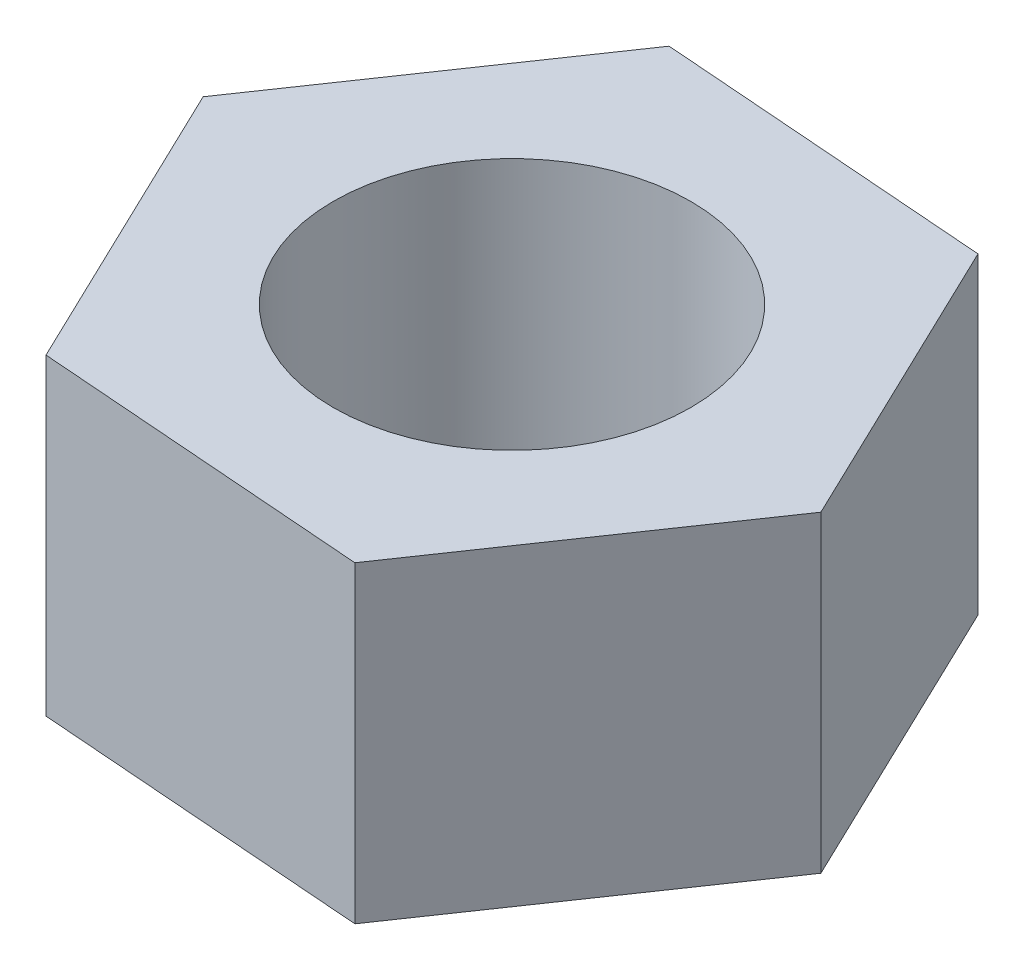
SolidWorks part; units mm, degrees
ref_plane "Спереди" through (0, 0, 0) normal (0, 0, 1) x (1, 0, 0)
ref_plane "Сверху" through (0, 0, 0) normal (0, 1, 0) x (1, 0, 0)
ref_plane "Справа" through (0, 0, 0) normal (1, 0, 0) x (0, 0, -1)
sketch "Эскиз1" plane through (0, 0, 0) normal (0, 1, 0) x (1, 0, 0)
  line L1 (3.2489, -6.766) -> (7.4839, -0.5694)
  line L2 (7.4839, -0.5694) -> (4.235, 6.1966)
  line L3 (4.235, 6.1966) -> (-3.2489, 6.766)
  line L4 (-3.2489, 6.766) -> (-7.4839, 0.5694)
  line L5 (-7.4839, 0.5694) -> (-4.235, -6.1966)
  line L6 (-4.235, -6.1966) -> (3.2489, -6.766)
  circle A0 centre (0, 0) radius 4
  circle A1 centre (0, 0) radius 6.5 construction
  dimension "D1" = 13
extrude "Вытянуть1" add sketch "Эскиз1" along normal blind 7
